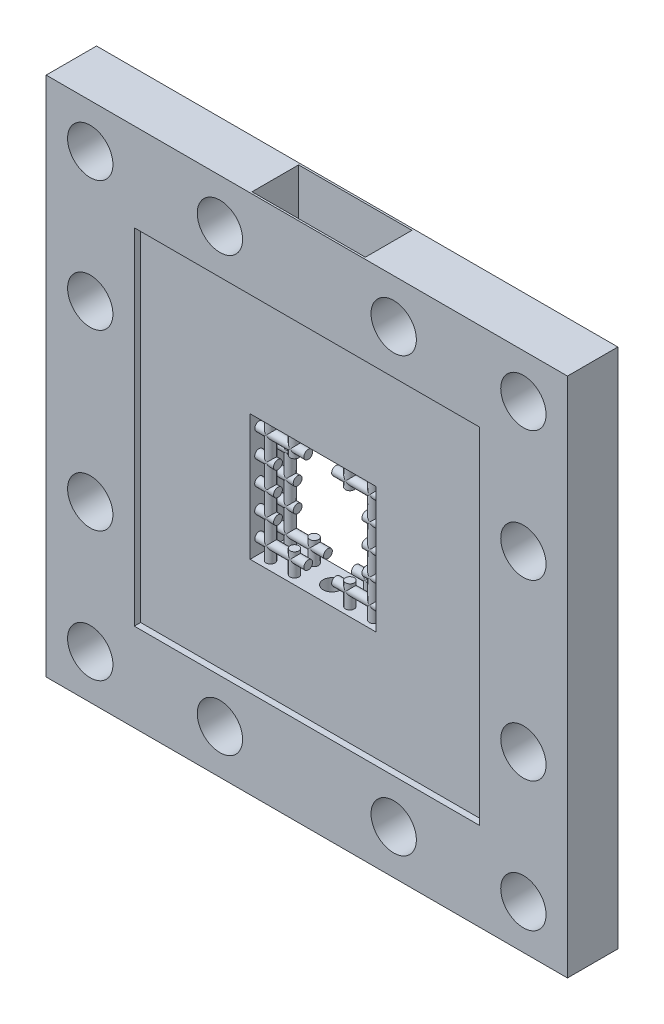
SolidWorks part; units mm, degrees
ref_plane "Front Plane" through (0, 0, 0) normal (0, 0, 1) x (1, 0, 0)
ref_plane "Top Plane" through (0, 0, 0) normal (0, 1, 0) x (1, 0, 0)
ref_plane "Right Plane" through (0, 0, 0) normal (1, 0, 0) x (0, 0, -1)
sketch "Sketch1" plane through (0, 0, 0) normal (0, 0, 1) x (1, 0, 0)
  line L1 (0, 0) -> (-20.7, 0)
  line L2 (0, 0) -> (0, 20.7)
  line L3 (0, 20.7) -> (-20.7, 20.7)
  line L4 (-20.7, 0) -> (-20.7, 20.7)
  dimension "D1" = 20.7
  dimension "D2" = 20.7
extrude "Boss-Extrude1" add sketch "Sketch1" along normal blind 2 contours L4 L3 L2 L1
sketch "Sketch6" plane through (0, 0, 0) normal (0, 0, 1) x (1, 0, 0)
  line L1 (0, 0) -> (-13.7, 0)
  line L2 (0, 0) -> (0, 13.7)
  line L3 (0, 13.7) -> (-13.7, 13.7)
  line L4 (-13.7, 0) -> (-13.7, 13.7)
  dimension "D1" = 13.7
  dimension "D2" = 13.7
extrude "Cut-Extrude1" cut sketch "Sketch6" along normal blind 0.5
sketch "Sketch10" plane through (0, 0, 0) normal (0, 0, 1) x (1, 0, 0)
  line L0 (-17.2, 0) -> (-17.2, 20.7) construction
  line L1 (0, 0) -> (-20.7, 0) construction
  line L2 (0, 20.7) -> (-20.7, 20.7) construction
  line L3 (-20.7, 0) -> (-20.7, 20.7) construction
  line L4 (0, 17.2) -> (-20.7, 17.2) construction
  line L5 (0, 0) -> (0, 20.7) construction
  line L6 (-20.7, 20.7) -> (0, 0) construction
  dimension "D1" = 3.5
  dimension "D2" = 3.5
sketch "Sketch11" plane through (0, 0, 0) normal (0, 0, 1) x (1, 0, 0)
  line L0 (-17.2, 0) -> (-17.2, 20.7) construction
  line L1 (-20.7, 20.7) -> (0, 0) construction
  circle A0 centre (-17.2, 17.2) radius 1.8
  dimension "D1" = 3.6
extrude "Cut-Extrude3" cut sketch "Sketch11" along normal blind 2
pattern_linear "LPattern1" count 2 spacing 10.3 along (0, -1, 0) of "Cut-Extrude3"
pattern_linear "LPattern2" count 2 spacing 10.3 along (1, 0, 0) of "Cut-Extrude3"
ref_plane "Plane5" through (0, 0, 2) normal (0, 0, 1) x (1, 0, 0)
mirror "Mirror4" about plane through (0, 0, 2) normal (0, 0, 1) of bodies 106
ref_plane "Plane7" through (0, 0, 0) normal (0, -1, 0) x (-1, 0, 0)
sketch "Sketch12" plane through (0, 0, 3.5) normal (0, 0, 1) x (1, 0, 0)
  line L0 (-20.7, 20.7) -> (0, 0) construction
  line L1 (5.0051, -5.0051) -> (-5.0051, -5.0051)
  line L2 (5.0051, -5.0051) -> (5.0051, 5.0051)
  line L3 (5.0051, 5.0051) -> (-5.0051, 5.0051)
  line L4 (-5.0051, -5.0051) -> (-5.0051, 5.0051)
  line L5 (5.0051, -5.0051) -> (-5.0051, 5.0051) construction
  line L6 (5.0051, 5.0051) -> (-5.0051, -5.0051) construction
  point P0 (0, 0)
extrude "Cut-Extrude4" cut sketch "Sketch12" against normal blind 4
ref_plane "Plane9" through (0, 20.7, 0) normal (0, 1, 0) x (1, 0, 0)
sketch "Sketch14" plane through (0, 20.7, 0) normal (0, 1, 0) x (1, 0, 0)
  circle A0 centre (0, -2.0016) radius 0.7
  dimension "D1" = 1.4
extrude "Cut-Extrude5" cut sketch "Sketch14" against normal blind 20.7
sketch "Sketch17" plane through (0, 20.7, 0) normal (0, 1, 0) x (1, 0, 0)
  line L1 (4.5, -0.1516) -> (-4.5, -0.1516)
  line L2 (4.5, -0.1516) -> (4.5, -3.8516)
  line L3 (4.5, -3.8516) -> (-4.5, -3.8516)
  line L4 (-4.5, -0.1516) -> (-4.5, -3.8516)
  line L5 (4.5, -0.1516) -> (-4.5, -3.8516) construction
  line L6 (4.5, -3.8516) -> (-4.5, -0.1516) construction
  point P0 (0, -2.0016)
  dimension "D1" = 9
  dimension "D2" = 3.7
extrude "Cut-Extrude6" cut sketch "Sketch17" against normal blind 5
mirror "Mirror7" about plane through (0, 0, 0) normal (0, -1, 0) of bodies 136 110
sketch "Sketch23" plane through (-5.0051, 0, 0) normal (1, 0, 0) x (0, 0, -1)
  line L0 (-2.2, 0) -> (2.2, 0) construction
  circle A0 centre (-1.225, 0) radius 0.35
extrude "Boss-Extrude2" add sketch "Sketch23" along normal blind 1.5
pattern_linear "LPattern3" count 2 spacing 1.56 along (0, 0, 1) of "Boss-Extrude2"
pattern_linear "LPattern4" count 2 spacing 1.9 along (0, -1, 0) count 2 spacing 1.9 along (0, 1, 0) of "Boss-Extrude2"
pattern_linear "LPattern5" count 2 spacing 1.9 along (0, -1, 0) count 2 spacing 1.9 along (0, 1, 0) of "LPattern3"
sketch "Sketch25" plane through (-5.0051, 0, 0) normal (1, 0, 0) x (0, 0, -1)
  circle A0 centre (-1.22, 3.8) radius 0.35
extrude "Boss-Extrude3" add sketch "Sketch25" along normal blind 3.9
pattern_linear "LPattern6" count 2 spacing 7.6 along (0, -1, 0) count 2 spacing 1.56 along (0, 0, 1) of "Boss-Extrude3"
sketch "Sketch26" plane through (0, 5.0051, 0) normal (0, -1, 0) x (1, 0, 0)
  circle A0 centre (-4.1, 1.22) radius 0.35
extrude "Boss-Extrude4" add sketch "Sketch26" along normal blind 10
pattern_linear "LPattern7" count 2 spacing 1.56 along (0, 0, 1) of "Boss-Extrude4"
sketch "Sketch27" plane through (0, -5.0051, 0) normal (0, 1, 0) x (1, 0, 0)
  circle A0 centre (-2.2, -1.22) radius 0.35
extrude "Boss-Extrude5" add sketch "Sketch27" along normal blind 1.8
pattern_linear "LPattern8" count 2 spacing 1.56 along (0, 0, 1) count 2 spacing 8.2 along (0, 1, 0) of "Boss-Extrude5"
mirror "Mirror9" about plane through (0, 0, 0) normal (1, 0, 0) of bodies 149 134
